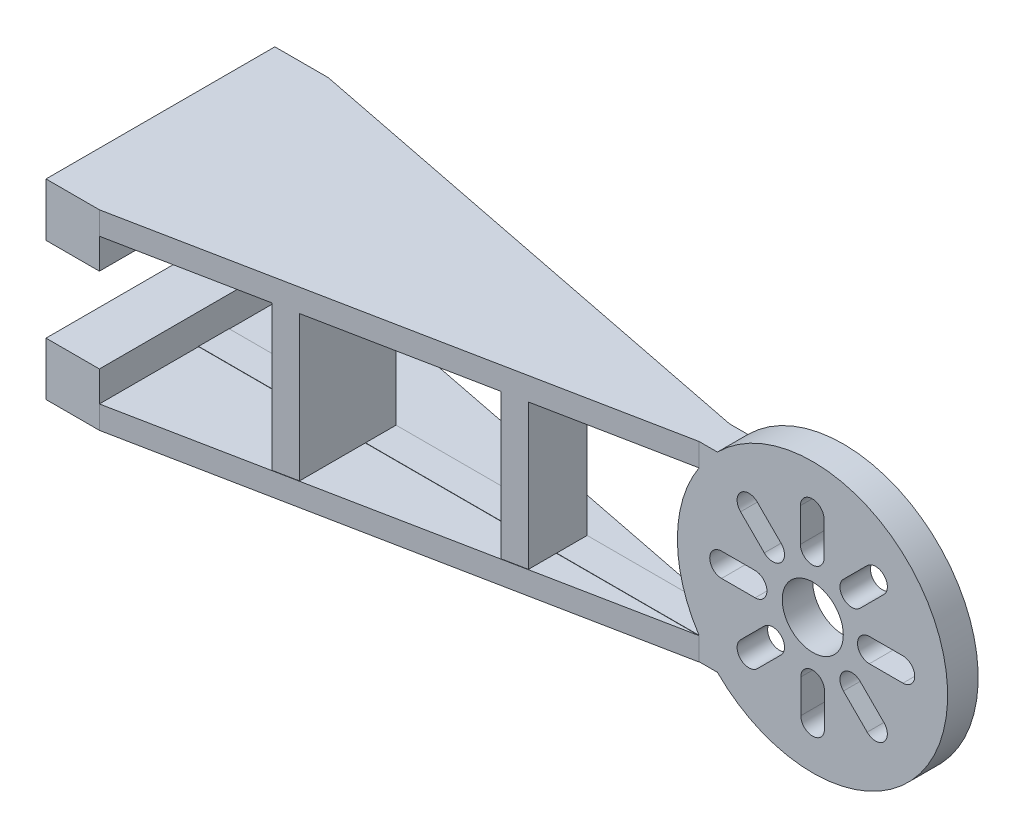
SolidWorks part; units mm, degrees
ref_plane "前视基准面" through (0, 0, 0) normal (0, 0, 1) x (1, 0, 0)
ref_plane "上视基准面" through (0, 0, 0) normal (0, 1, 0) x (1, 0, 0)
ref_plane "右视基准面" through (0, 0, 0) normal (1, 0, 0) x (0, 0, -1)
sketch "草图1" plane through (0, 0, 0) normal (0, 0, 1) x (1, 0, 0)
  line L0 (-39.929, 12.519) -> (-39.929, 9.519)
  line L1 (-39.929, 12.519) -> (28.071, 12.519)
  line L3 (-39.929, -12.481) -> (28.071, -12.481)
  line L7 (-39.929, 9.519) -> (25.663, 9.519)
  line L8 (-39.929, -12.481) -> (-39.929, -9.481)
  line L9 (-39.929, -9.481) -> (25.663, -9.481)
  line L10 (28.6144, 0) -> (33.0144, 0) construction
  line L11 (33.0144, 0) -> (28.6144, 0) construction
  line L12 (28.6144, 1.55) -> (33.0144, 1.55)
  line L13 (28.6144, -1.55) -> (33.0144, -1.55)
  line L14 (52.3856, 0) -> (47.9856, 0) construction
  line L15 (52.3856, 1.55) -> (47.9856, 1.55)
  line L16 (52.3856, -1.55) -> (47.9856, -1.55)
  line L18 (40.552, -11.9376) -> (40.552, -7.5376) construction
  line L19 (42.102, -11.9376) -> (42.102, -7.5376)
  line L20 (39.002, -11.9376) -> (39.002, -7.5376)
  line L21 (32.2034, 8.3597) -> (35.3147, 5.2485) construction
  line L22 (33.2994, 9.4557) -> (36.4107, 6.3445)
  line L23 (31.1074, 7.2637) -> (34.2186, 4.1524)
  line L24 (40.5, 11.8856) -> (40.5, 7.4856) construction
  line L25 (42.05, 11.8856) -> (42.05, 7.4856)
  line L26 (38.95, 11.8856) -> (38.95, 7.4856)
  line L27 (48.7966, 8.3597) -> (45.6853, 5.2485) construction
  line L28 (47.7006, 9.4557) -> (44.5893, 6.3445)
  line L29 (49.8926, 7.2637) -> (46.7814, 4.1524)
  line L31 (32.2034, -8.3597) -> (35.3147, -5.2485) construction
  line L32 (33.2994, -9.4557) -> (36.4107, -6.3445)
  line L33 (31.1074, -7.2637) -> (34.2186, -4.1524)
  line L34 (48.7966, -8.3597) -> (45.6853, -5.2485) construction
  line L35 (47.7006, -9.4557) -> (44.5893, -6.3445)
  line L36 (49.8926, -7.2637) -> (46.7814, -4.1524)
  arc A4 (28.071, 12.519) -> (28.071, -12.481) centre (40.571, 0.019) cw
  arc A5 (25.663, 9.519) -> (25.663, -9.481) centre (40.1458, 0.019) ccw
  circle A6 centre (40.571, 0.019) radius 4
  arc A7 (28.6144, 1.55) -> (28.6144, -1.55) centre (28.6144, 0) ccw
  arc A8 (33.0144, -1.55) -> (33.0144, 1.55) centre (33.0144, 0) ccw
  arc A9 (52.3856, 1.55) -> (52.3856, -1.55) centre (52.3856, 0) cw
  arc A10 (47.9856, -1.55) -> (47.9856, 1.55) centre (47.9856, 0) cw
  arc A11 (42.102, -11.9376) -> (39.002, -11.9376) centre (40.552, -11.9376) cw
  arc A12 (39.002, -7.5376) -> (42.102, -7.5376) centre (40.552, -7.5376) cw
  arc A13 (33.2994, 9.4557) -> (31.1074, 7.2637) centre (32.2034, 8.3597) ccw
  arc A14 (34.2186, 4.1524) -> (36.4107, 6.3445) centre (35.3147, 5.2485) ccw
  arc A15 (42.05, 11.8856) -> (38.95, 11.8856) centre (40.5, 11.8856) ccw
  arc A16 (38.95, 7.4856) -> (42.05, 7.4856) centre (40.5, 7.4856) ccw
  arc A17 (47.7006, 9.4557) -> (49.8926, 7.2637) centre (48.7966, 8.3597) cw
  arc A18 (46.7814, 4.1524) -> (44.5893, 6.3445) centre (45.6853, 5.2485) cw
  arc A19 (33.2994, -9.4557) -> (31.1074, -7.2637) centre (32.2034, -8.3597) cw
  arc A20 (34.2186, -4.1524) -> (36.4107, -6.3445) centre (35.3147, -5.2485) cw
  arc A21 (47.7006, -9.4557) -> (49.8926, -7.2637) centre (48.7966, -8.3597) ccw
  arc A22 (46.7814, -4.1524) -> (44.5893, -6.3445) centre (45.6853, -5.2485) ccw
  point P0 (0, 0)
  point P14 (40.5, 0)
  point P18 (30.8144, 0)
  point P23 (27.0644, 0)
  point P24 (34.5644, 0)
  point P27 (50.1856, 0)
  point P35 (40.552, -9.7376)
  point P42 (33.759, 6.8041)
  point P50 (40.5, 9.6856)
  point P57 (47.241, 6.8041)
  point P65 (33.759, -6.8041)
  point P72 (47.241, -6.8041)
  dimension "D1" = 7.5
extrude "凸台-拉伸3" add sketch "草图1" along normal blind 4
sketch "草图2" plane through (0, 12.519, 0) normal (0, 1, 0) x (1, 0, 0)
  line L5 (-39.929, 0) -> (-39.929, 13)
  line L6 (-39.929, -4) -> (-39.929, 0) construction
  line L7 (-39.929, 0) -> (28.071, 0) construction
  line L8 (-39.929, 0) -> (25.661, 0)
  line L9 (28.071, 0) -> (-39.929, 0) construction
  line L10 (-39.929, 13) -> (25.661, 0)
extrude "凸台-拉伸5" add sketch "草图2" against normal blind 3 contours L10 L8 L5
mirror "镜向1" about plane through (0, 0, 0) normal (0, 1, 0) of "凸台-拉伸5"
sketch "草图5" plane through (0, 12.519, 0) normal (0, 1, 0) x (1, 0, 0)
  line L0 (-39.929, -4) -> (-39.929, -17)
  line L1 (-39.929, -4) -> (25.661, -4)
  line L2 (28.071, -4) -> (-39.929, -4) construction
  line L3 (-39.929, -17) -> (25.661, -4)
extrude "凸台-拉伸6" add sketch "草图5" against normal blind 3 contours L3 L1 L0
mirror "镜向2" about plane through (0, 0, 0) normal (0, 1, 0) of "凸台-拉伸6"
sketch "草图7" plane through (-39.929, 0, 0) normal (-1, 0, 0) x (0, 0, 1)
  line L1 (-13, 12.519) -> (16.9978, 12.519)
  line L2 (-13, 12.519) -> (-13, 5.5476)
  line L3 (-13, 5.5476) -> (16.9978, 5.5476)
  line L4 (16.9978, 12.519) -> (16.9978, 5.5476)
extrude "凸台-拉伸7" add sketch "草图7" along normal blind 7 contours L2 L1 L4 L3
mirror "镜向3" about plane through (0, 0, 0) normal (0, 1, 0) of "凸台-拉伸7"
sketch "草图8" plane through (0, 9.519, 0) normal (0, -1, 0) x (1, 0, 0)
  line L0 (-21.0397, 0) -> (-18.0397, 0)
  line L1 (-39.929, 0) -> (25.663, 0) construction
  line L2 (-21.0397, 0) -> (-21.0397, 13.2561)
  line L3 (-39.929, 17) -> (25.661, 4) construction
  line L4 (-21.0397, 13.2561) -> (-18.0397, 12.6615)
  line L5 (-18.0397, 12.6615) -> (-18.0397, 0)
  line L6 (-46.929, -13) -> (-39.929, -13) construction
extrude "凸台-拉伸8" add sketch "草图8" along normal blind 19 contours L5 L0 L2 L4
sketch "草图9" plane through (0, 9.519, 0) normal (0, -1, 0) x (1, 0, 0)
  line L0 (4, 0) -> (7, 0)
  line L1 (-39.929, 0) -> (25.663, 0) construction
  line L2 (4, 0) -> (4, 8.2932)
  line L3 (-39.929, 17) -> (25.661, 4) construction
  line L4 (4, 8.2932) -> (7, 7.6986)
  line L5 (7, 7.6986) -> (7, 0)
extrude "凸台-拉伸9" add sketch "草图9" along normal blind 19
